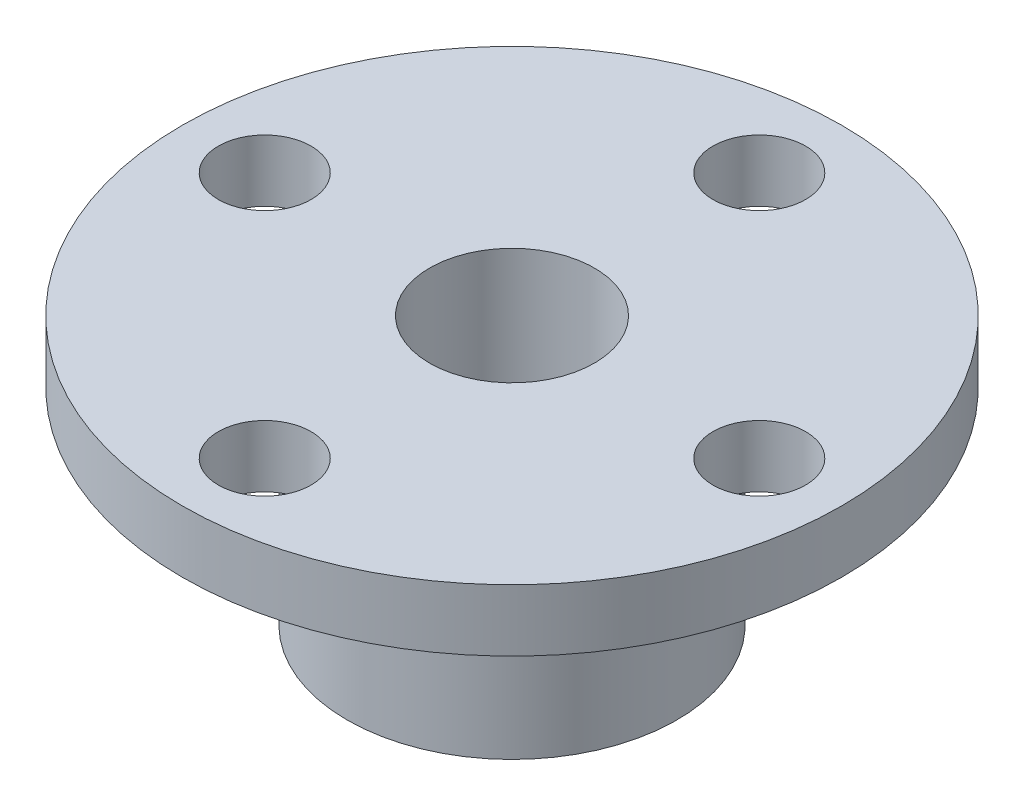
SolidWorks part; units mm, degrees
ref_plane "Front" through (0, 0, 0) normal (0, 0, 1) x (1, 0, 0)
ref_plane "Top" through (0, 0, 0) normal (0, 1, 0) x (1, 0, 0)
ref_plane "Right" through (0, 0, 0) normal (1, 0, 0) x (0, 0, -1)
sketch "Sketch1" plane through (0, 0, 0) normal (0, 1, 0) x (1, 0, 0)
  circle A0 centre (0, 0) radius 8
  circle A1 centre (0, 0) radius 4
  dimension "D1" = 16
  dimension "D2" = 8
extrude "Boss-Extrude1" add sketch "Sketch1" along normal mid plane 10 contours A0
sketch "Sketch2" plane through (0, 5, 0) normal (0, 1, 0) x (1, 0, 0)
  circle A0 centre (0, 0) radius 4 construction
  circle A1 centre (0, 0) radius 4
  circle A2 centre (0, 0) radius 16
  dimension "D1" = 32
extrude "Boss-Extrude2" add sketch "Sketch2" along normal blind 3
ref_plane "Plane1" through (-8, 0, 0) normal (-1, 0, 0) x (0, 0, 1)
sketch "Sketch3" plane through (-8, 0, 0) normal (-1, 0, 0) x (0, 0, 1)
  point P0 (0, 0)
hole_wizard "M4x0.7 Tapped Hole1" positions "Sketch4" profile "Sketch6" tap size "M4x0.7" standard "ANSI Metric"
sketch "Sketch4" plane through (-8, 0, 0) normal (-1, 0, 0) x (0, 0, 1)
  point P0 (0, 0)
sketch "Sketch6" plane through (-8, 0, 0) normal (0, 1, 0) x (0, 0, 1)
  line L0 (0, 0) -> (0, 4)
  line L1 (0, 4) -> (1.65, 4)
  line L2 (1.65, 4) -> (1.65, 0)
  line L5 (1.65, 0) -> (0, 0)
  line L11 (0, -6.35) -> (0, 107.95) construction
  dimension "Thru Tap Drill Dia." = 3.3
  dimension "Thru Tap Drill Depth" = 4
cosmetic thread "Hole Thread1"
sketch "Sketch7" plane through (0, 8, 0) normal (0, 1, 0) x (1, 0, 0)
  circle A0 centre (0, 0) radius 12 construction
  point P3 (-12, 0)
  point P4 (12, 0)
  point P5 (0, -12)
  point P6 (0, 12)
  dimension "D1" = 24
hole_wizard "M4 Clearance Hole1" positions "Sketch8" profile "Sketch9" hole size "M4" standard "ANSI Metric" end condition up to next
sketch "Sketch8" plane through (0, 8, 0) normal (0, 1, 0) x (1, 0, 0)
  point P0 (0, 12)
  point P3 (12, 0)
  point P6 (-12, 0)
  point P9 (0, -12)
sketch "Sketch9" plane through (0, 8, -12) normal (1, 0, 0) x (0, 0, 1)
  line L0 (0, 0) -> (0, 3)
  line L1 (0, 3) -> (2.25, 3)
  line L2 (2.25, 3) -> (2.25, 0)
  line L5 (2.25, 0) -> (0, 0)
  line L11 (0, -6.35) -> (0, 107.95) construction
  dimension "Thru Hole Dia." = 4.5
  dimension "Thru Hole Depth" = 3
